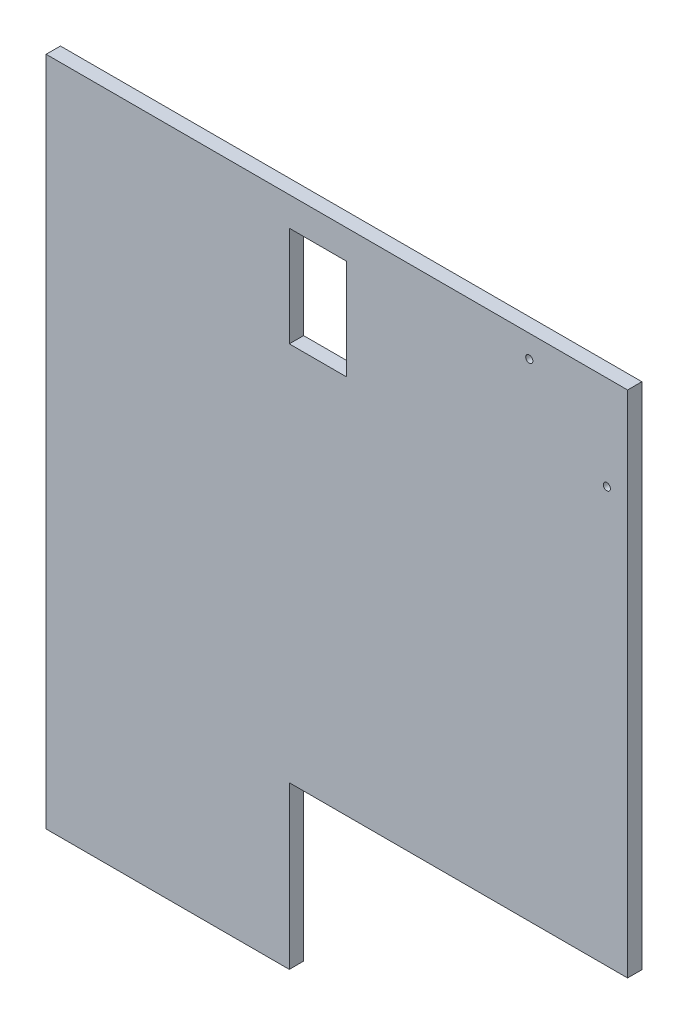
SolidWorks part; units mm, degrees
ref_plane "Спереди" through (0, 0, 0) normal (0, 0, 1) x (1, 0, 0)
ref_plane "Сверху" through (0, 0, 0) normal (0, 1, 0) x (1, 0, 0)
ref_plane "Справа" through (0, 0, 0) normal (1, 0, 0) x (0, 0, -1)
sketch "Эскиз1" plane through (0, 0, 0) normal (0, 0, 1) x (1, 0, 0)
  line L0 (0, 0) -> (8127, 0)
  line L1 (8127, 0) -> (8127, -7118)
  line L2 (8127, -7118) -> (3399, -7118)
  line L3 (3399, -7118) -> (3399, -9378)
  line L4 (3399, -9378) -> (0, -9378)
  line L5 (0, -9378) -> (0, 0)
  line L6 (8127, -6918) -> (8127, -203) construction
  line L7 (3399, -7118) -> (7924, -7118) construction
  line L8 (203, -9378) -> (3199, -9378) construction
  line L9 (3399, -1706) -> (3399, -203) construction
  line L10 (3399, -406) -> (4199, -406)
  line L11 (3399, -406) -> (3399, -1806)
  line L12 (3399, -1806) -> (4199, -1806)
  line L13 (4199, -406) -> (4199, -1806)
  line L14 (5027, -1806) -> (7924, -1806) construction
  circle A0 centre (7837.4107, -1315.3204) radius 50
  circle A1 centre (6753.1695, -313.5068) radius 50
  dimension "D3" = 100
  dimension "D1" = 800
  dimension "D2" = 1400
extrude "Бобышка-Вытянуть1" add sketch "Эскиз1" against normal blind 200
